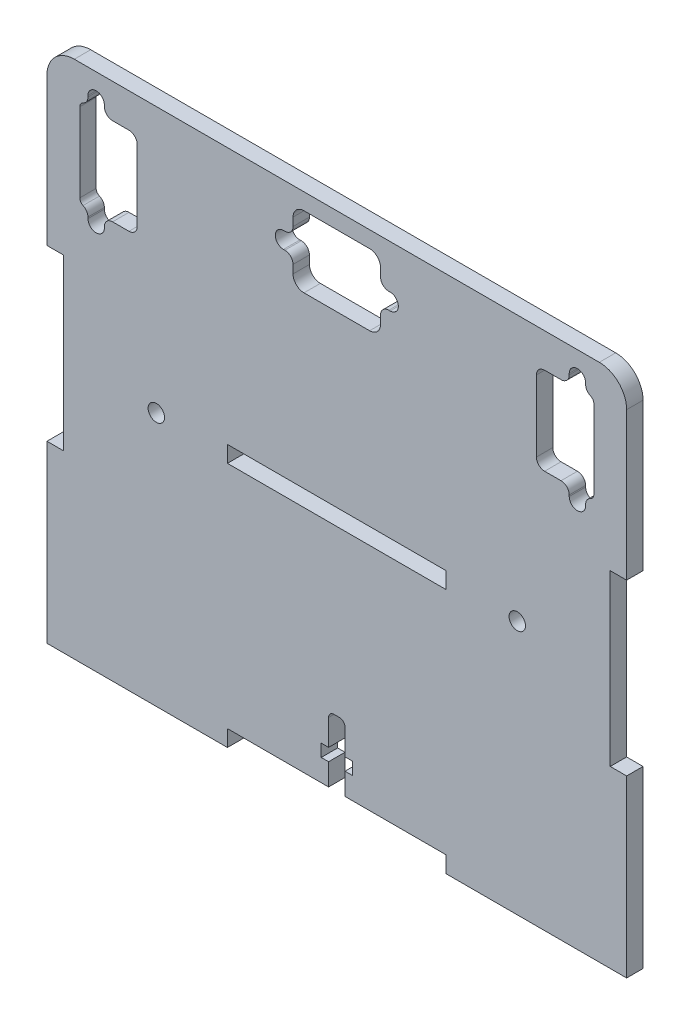
SolidWorks part; units mm, degrees
other "Marcação1"
sketch "Esboço7" plane through (-68, 31.5, 3) normal (-0.6758, 0.2828, 0.6807) x (0.7271, 0.1043, 0.6785)
sketch "Esboço8" plane through (-68, 31.5, 3) normal (-0.6758, 0.2828, 0.6807) x (0.7271, 0.1043, 0.6785)
sketch "Esboço9" plane through (-60.5, 31.5, 3) normal (-0.6758, 0.2828, 0.6807) x (0.7271, 0.1043, 0.6785)
sketch "Esboço11" plane through (-60.5, 31.5, 3) normal (-0.6758, 0.2828, 0.6807) x (0.7271, 0.1043, 0.6785)
sketch "Esboço13" plane through (-60.5, 36.25, 3) normal (-0.6758, 0.2828, 0.6807) x (0.7271, 0.1043, 0.6785)
sketch "Esboço14" plane through (-60.5, 36.25, 3) normal (-0.6758, 0.2828, 0.6807) x (0.7271, 0.1043, 0.6785)
sketch "Esboço17" plane through (-60.5, 36.25, 3) normal (-0.6758, 0.2828, 0.6807) x (0.7271, 0.1043, 0.6785)
sketch "Esboço18" plane through (-60.5, 51.25, 3) normal (-0.6758, 0.2828, 0.6807) x (0.7271, 0.1043, 0.6785)
sketch "Esboço19" plane through (-60.5, 51.25, 3) normal (-0.6758, 0.2828, 0.6807) x (0.7271, 0.1043, 0.6785)
sketch "Esboço20" plane through (-60.5, 51.25, 3) normal (-0.6758, 0.2828, 0.6807) x (0.7271, 0.1043, 0.6785)
material "Acrylic (Medium-high impact)"
ref_plane "Plano frontal" through (0, 0, 0) normal (0, 0, 1) x (1, 0, 0)
ref_plane "Plano superior" through (0, 0, 0) normal (0, 1, 0) x (1, 0, 0)
ref_plane "Plano direito" through (0, 0, 0) normal (1, 0, 0) x (0, 0, -1)
sketch "Esboço1" plane through (0, 0, 0) normal (0, 0, 1) x (1, 0, 0)
  line L1 (-50, -47.5) -> (50, -47.5)
  line L2 (-50, -47.5) -> (-50, 47.5)
  line L3 (-50, 47.5) -> (50, 47.5)
  line L4 (50, -47.5) -> (50, 47.5)
  line L5 (-50, -47.5) -> (50, 47.5) construction
  line L6 (-50, 47.5) -> (50, -47.5) construction
  point P0 (0, 0)
  dimension "D1" = 100
  dimension "D2" = 95
extrude "Ressalto-extrusão1" add sketch "Esboço1" along normal mid plane 3
sketch "Esboço2" plane through (0, 0, 1.5) normal (0, 0, 1) x (1, 0, 0)
  line L1 (-20, -47.5) -> (20, -47.5)
  line L2 (-20, -47.5) -> (-20, -44.5)
  line L3 (-20, -44.5) -> (20, -44.5)
  line L4 (20, -47.5) -> (20, -44.5)
  line L6 (-50, -47.5) -> (50, -47.5) construction
  line L7 (0, -1.65) -> (0, 1.65) construction
  line L21 (-20, 0.5) -> (20, 0.5)
  line L22 (-20, 0.5) -> (-20, -2.5)
  line L23 (-20, -2.5) -> (20, -2.5)
  line L24 (20, 0.5) -> (20, -2.5)
  line L25 (-20, 0.5) -> (20, -2.5) construction
  line L26 (-20, -2.5) -> (20, 0.5) construction
  circle A2 centre (-33, -1) radius 1.5
  circle A4 centre (33, -1) radius 1.5
  point P6 (0, -44.5)
  point P14 (0, -1)
  dimension "D4" = 3
  dimension "D8" = 3
  dimension "D5" = 13
  dimension "D2" = 40
  dimension "D3" = 45
  dimension "D6" = 3
  dimension "D13" = 40
extrude "Corte-extrusão1" cut sketch "Esboço2" against normal through all
sketch "Esboço3" plane through (0, 0, 1.5) normal (0, 0, 1) x (1, 0, 0)
  line L0 (-50, 47.5) -> (-50, -47.5) construction
  line L1 (-50, -15.5) -> (-53, -15.5)
  line L2 (-50, -15.5) -> (-50, -47.5)
  line L3 (-50, -47.5) -> (-53, -47.5)
  line L4 (-53, -15.5) -> (-53, -47.5)
  line L5 (0, -1.65) -> (0, 1.65) construction
  line L6 (50, -47.5) -> (53, -47.5)
  line L7 (50, -15.5) -> (53, -15.5)
  line L8 (50, -15.5) -> (50, -47.5)
  line L9 (53, -15.5) -> (53, -47.5)
  line L10 (-50, -47.5) -> (-20, -47.5) construction
  line L11 (50, 47.5) -> (-50, 47.5) construction
  line L16 (-53, 15.5) -> (-53, 47.5)
  line L17 (-50, 47.5) -> (-53, 47.5)
  line L18 (-50, 15.5) -> (-50, 47.5)
  line L19 (-50, 15.5) -> (-53, 15.5)
  line L20 (50, -47.5) -> (50, 47.5) construction
  line L21 (50, 15.5) -> (53, 15.5)
  line L22 (50, 15.5) -> (50, 47.5)
  line L23 (50, 47.5) -> (53, 47.5)
  line L24 (53, 15.5) -> (53, 47.5)
  line L25 (93.1741, 0) -> (-93.1741, 0) construction
  line L26 (0, -62.7565) -> (0, 62.7565) construction
  point P31 (0, 0)
  point P38 (0, 0)
  dimension "D1" = 3
  dimension "D2" = 31
  dimension "D4" = 3
  dimension "D5" = 53
extrude "Ressalto-extrusão2" add sketch "Esboço3" against normal through all
sketch "Sketch1" plane through (0, 0, -1.5) normal (0, 0, -1) x (-1, 0, 0)
  line L1 (-50.5, 33.25) -> (-36.5, 33.25) construction
  line L6 (-49, 41.25) -> (-47, 41.25) construction
  line L12 (-50.5, 39.75) -> (-50.5, 26.75) construction
  line L13 (-53, 47.5) -> (53, 47.5) construction
  line L14 (-49, 25.25) -> (-47, 25.25) construction
  line L15 (-36.5, 39.75) -> (-36.5, 26.75)
  line L16 (-45.5, 23.5) -> (-45.5, 23.75)
  line L17 (-42.5, 23.5) -> (-42.5, 23.75)
  line L18 (-41, 25.25) -> (-38, 25.25)
  line L19 (-45.5, 43) -> (-45.5, 42.75)
  line L20 (-42.5, 43) -> (-42.5, 42.75)
  line L21 (-41, 41.25) -> (-38, 41.25)
  line L22 (-53, 47.5) -> (53, 47.5) construction
  line L24 (0, 1.65) -> (0, -1.65) construction
  line L35 (0, 44.5) -> (0, 31.5) construction
  line L36 (-6, 44.5) -> (6, 44.5)
  line L37 (-8, 42.5) -> (-8, 41)
  line L38 (-6, 31.5) -> (6, 31.5)
  line L39 (8, 42.5) -> (8, 41)
  line L40 (-9.75, 39.5) -> (-9.5, 39.5)
  line L41 (-9.75, 36.5) -> (-9.5, 36.5)
  line L42 (-8, 35) -> (-8, 33.5)
  line L43 (9.75, 39.5) -> (9.5, 39.5)
  line L44 (9.75, 36.5) -> (9.5, 36.5)
  line L45 (8, 35) -> (8, 33.5)
  line L46 (-47, 40.4587) -> (-47, 26.0413)
  line L47 (-50, -15.5) -> (-50, 15.5) construction
  line L48 (49, 25.25) -> (47, 25.25) construction
  line L49 (50.5, 39.75) -> (50.5, 26.75) construction
  line L50 (49, 41.25) -> (47, 41.25) construction
  line L51 (50.5, 33.25) -> (36.5, 33.25) construction
  line L52 (47, 40.4587) -> (47, 26.0413)
  line L53 (41, 41.25) -> (38, 41.25)
  line L54 (42.5, 43) -> (42.5, 42.75)
  line L55 (45.5, 43) -> (45.5, 42.75)
  line L56 (41, 25.25) -> (38, 25.25)
  line L57 (42.5, 23.5) -> (42.5, 23.75)
  line L58 (45.5, 23.5) -> (45.5, 23.75)
  line L59 (36.5, 39.75) -> (36.5, 26.75)
  arc A0 (-42.5, 43) -> (-45.5, 43) centre (-44, 43) ccw
  arc A1 (-45.5, 23.5) -> (-42.5, 23.5) centre (-44, 23.5) ccw
  arc A2 (-42.5, 23.75) -> (-41, 25.25) centre (-41, 23.75) cw
  arc A3 (-45.5, 23.75) -> (-46.4, 25.1248) centre (-47, 23.75) ccw
  arc A4 (-42.5, 42.75) -> (-41, 41.25) centre (-41, 42.75) ccw
  arc A5 (-45.5, 42.75) -> (-46.4, 41.3752) centre (-47, 42.75) cw
  arc A6 (-50.5, 26.75) -> (-49, 25.25) centre (-49, 26.75) ccw construction
  arc A7 (-38, 25.25) -> (-36.5, 26.75) centre (-38, 26.75) ccw
  arc A8 (-38, 41.25) -> (-36.5, 39.75) centre (-38, 39.75) cw
  arc A9 (-49, 41.25) -> (-50.5, 39.75) centre (-49, 39.75) ccw construction
  arc A20 (-9.75, 39.5) -> (-9.75, 36.5) centre (-9.75, 38) ccw
  arc A21 (9.75, 36.5) -> (9.75, 39.5) centre (9.75, 38) ccw
  arc A22 (-9.5, 36.5) -> (-8, 35) centre (-9.5, 35) cw
  arc A23 (-9.5, 39.5) -> (-8, 41) centre (-9.5, 41) ccw
  arc A24 (9.5, 36.5) -> (8, 35) centre (9.5, 35) ccw
  arc A25 (9.5, 39.5) -> (8, 41) centre (9.5, 41) cw
  arc A26 (-8, 33.5) -> (-6, 31.5) centre (-6, 33.5) ccw
  arc A27 (6, 31.5) -> (8, 33.5) centre (6, 33.5) ccw
  arc A28 (6, 44.5) -> (8, 42.5) centre (6, 42.5) cw
  arc A29 (-6, 44.5) -> (-8, 42.5) centre (-6, 42.5) ccw
  arc A30 (-47, 26.0413) -> (-46.4, 25.1248) centre (-46, 26.0413) ccw
  arc A31 (-47, 40.4587) -> (-46.4, 41.3752) centre (-46, 40.4587) cw
  arc A32 (49, 41.25) -> (50.5, 39.75) centre (49, 39.75) cw construction
  arc A33 (50.5, 26.75) -> (49, 25.25) centre (49, 26.75) cw construction
  arc A34 (47, 40.4587) -> (46.4, 41.3752) centre (46, 40.4587) ccw
  arc A35 (47, 26.0413) -> (46.4, 25.1248) centre (46, 26.0413) cw
  arc A36 (38, 41.25) -> (36.5, 39.75) centre (38, 39.75) ccw
  arc A37 (38, 25.25) -> (36.5, 26.75) centre (38, 26.75) cw
  arc A38 (45.5, 42.75) -> (46.4, 41.3752) centre (47, 42.75) ccw
  arc A39 (42.5, 42.75) -> (41, 41.25) centre (41, 42.75) cw
  arc A40 (45.5, 23.75) -> (46.4, 25.1248) centre (47, 23.75) cw
  arc A41 (42.5, 23.75) -> (41, 25.25) centre (41, 23.75) ccw
  arc A42 (45.5, 23.5) -> (42.5, 23.5) centre (44, 23.5) cw
  arc A43 (42.5, 43) -> (45.5, 43) centre (44, 43) cw
  point P8 (-42.5, 25.25)
  point P21 (-45.5, 25.25)
  point P24 (-42.5, 41.25)
  point P29 (-50.5, 25.25)
  point P34 (-36.5, 41.25)
  point P37 (-50.5, 41.25)
  point P86 (0, 31.5)
  point P99 (-8, 36.5)
  point P107 (8, 36.5)
  point P112 (-8, 31.5)
  point P117 (8, 44.5)
  point P120 (-8, 44.5)
  point P127 (50.5, 41.25)
  point P128 (36.5, 41.25)
  point P129 (50.5, 25.25)
  point P130 (42.5, 41.25)
  point P131 (45.5, 25.25)
  point P132 (42.5, 25.25)
  dimension "D1" = 16
  dimension "D3" = 3
  dimension "D5" = 1.5
  dimension "D6" = 1.5
  dimension "D7" = 3
  dimension "D8" = 3
  dimension "D9" = 5
  dimension "D4" = 19.5
  dimension "D12" = 19.5
  dimension "D13" = 3
  dimension "D15" = 1.5
  dimension "D16" = 1.5
  dimension "D14" = 2
  dimension "D18" = 1
  dimension "D10" = 16
  dimension "D11" = 13
  dimension "D17" = 5
  dimension "D19" = 3
  dimension "D20" = 7.5
extrude "Cut-Extrude1" cut sketch "Sketch1" against normal through all both and the other way through all
sketch "Sketch2" plane through (0, 0, 0) normal (0, 0, 1) x (1, 0, 0)
  line L0 (20, -44.5) -> (-20, -44.5) construction
  line L1 (-0.5, -32.5) -> (0.5, -32.5)
  line L2 (-1.5, -33.5) -> (-1.5, -38.23)
  line L3 (-1.5, -44.5) -> (1.5, -44.5)
  line L4 (1.5, -33.5) -> (1.5, -38.23)
  line L5 (1.5, -38.23) -> (2.85, -38.23)
  line L6 (-2.85, -38.23) -> (-1.5, -38.23)
  line L7 (-2.85, -38.23) -> (-2.85, -40.5)
  line L8 (-2.85, -40.5) -> (-1.5, -40.5)
  line L9 (2.85, -38.23) -> (2.85, -40.5)
  line L10 (-1.5, -40.5) -> (-1.5, -44.5)
  line L11 (1.5, -40.5) -> (2.85, -40.5)
  line L12 (1.5, -40.5) -> (1.5, -44.5)
  arc A0 (0.5, -32.5) -> (1.5, -33.5) centre (0.5, -33.5) cw
  arc A1 (-0.5, -32.5) -> (-1.5, -33.5) centre (-0.5, -33.5) ccw
  point P6 (0, -32.5)
  point P18 (1.5, -32.5)
  point P21 (-1.5, -32.5)
  dimension "D7" = 1
  dimension "D1" = 3
  dimension "D2" = 12
  dimension "D3" = 2.27
  dimension "D4" = 1.35
  dimension "D5" = 1.35
  dimension "D6" = 4
extrude "Cut-Extrude4" cut sketch "Sketch2" against normal through all both and the other way through all
fillet "Fillet1" radius 5 2 edges at (53, 47.5, 0) (-53, 47.5, 0)
sketch "Esboço12" plane through (0, 0, 1.5) normal (0, 0, 1) x (1, 0, 0)
  line L8 (-20, -1) -> (20, -1) construction
  line L9 (-20, 0.5) -> (-20, -2.5) construction
  line L10 (20, -2.5) -> (20, 0.5) construction
  line L12 (0, -20.25) -> (0, -22.75) construction
  line L15 (-11.5, -20.25) -> (11.5, -20.25)
  line L16 (-12.5, -21.25) -> (-12.5, -21.75)
  line L17 (-11.5, -22.75) -> (11.5, -22.75)
  line L18 (12.5, -21.25) -> (12.5, -21.75)
  line L19 (-12.5, -20.25) -> (12.5, -22.75) construction
  line L20 (-12.5, -22.75) -> (12.5, -20.25) construction
  circle A0 centre (-10.5, -7.25) radius 1
  circle A1 centre (10.5, -7.25) radius 1
  circle A2 centre (10.5, 5.25) radius 1
  circle A3 centre (-10.5, 5.25) radius 1
  arc A4 (11.5, -22.75) -> (12.5, -21.75) centre (11.5, -21.75) ccw
  arc A5 (11.5, -20.25) -> (12.5, -21.25) centre (11.5, -21.25) cw
  arc A6 (-11.5, -20.25) -> (-12.5, -21.25) centre (-11.5, -21.25) ccw
  arc A7 (-12.5, -21.75) -> (-11.5, -22.75) centre (-11.5, -21.75) ccw
  point P35 (0, -21.5)
  dimension "D4" = 2
  dimension "D5" = 13
  dimension "D8" = 12.5
  dimension "D2" = 1
  dimension "D9" = 21
  dimension "D10" = 25
  dimension "D11" = 2.5
extrude "Corte-extrusão3" [suppressed] cut sketch "Esboço12" against normal through all
